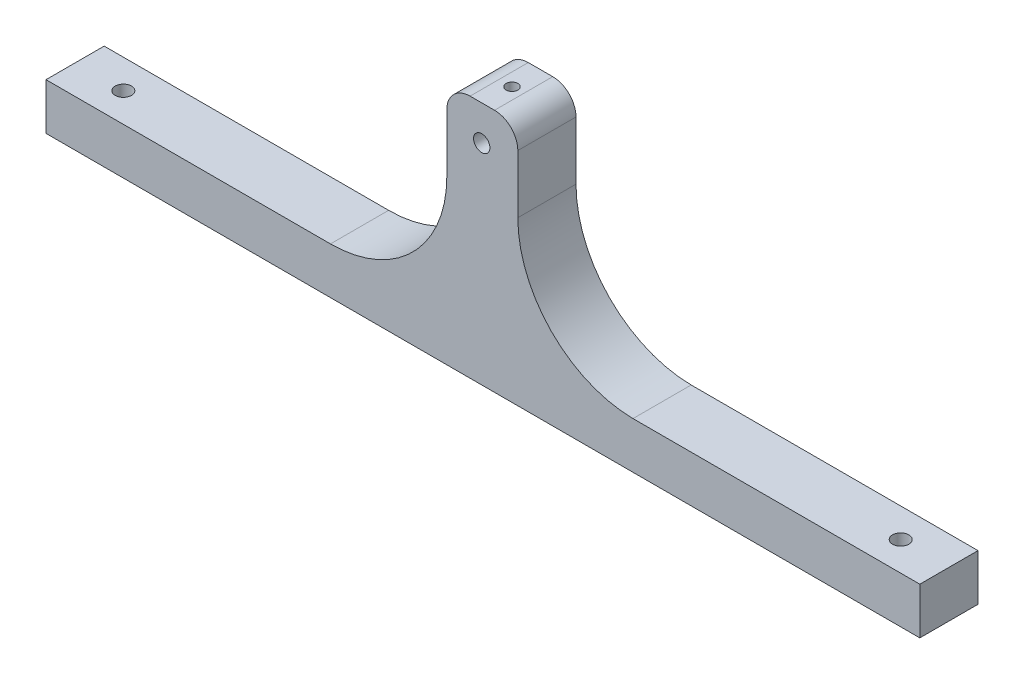
SolidWorks part; units mm, degrees
ref_plane "Front Plane" through (0, 0, 0) normal (0, 0, 1) x (1, 0, 0)
ref_plane "Top Plane" through (0, 0, 0) normal (0, 1, 0) x (1, 0, 0)
ref_plane "Right Plane" through (0, 0, 0) normal (1, 0, 0) x (0, 0, -1)
sketch "Sketch1" plane through (0, 0, 0) normal (0, 1, 0) x (1, 0, 0)
  line L0 (-37.55, 0) -> (37.55, 0) construction
  line L1 (-37.55, -2.5) -> (37.55, -2.5)
  line L2 (-37.55, -2.5) -> (-37.55, 2.5)
  line L3 (-37.55, 2.5) -> (37.55, 2.5)
  line L4 (37.55, -2.5) -> (37.55, 2.5)
  line L7 (0, 2.5) -> (0, -2.5) construction
  line L8 (-33.405, 2.5) -> (-33.405, -2.5) construction
  line L9 (33.405, 2.5) -> (33.405, -2.5) construction
  circle A0 centre (-33.405, 0) radius 0.7
  circle A1 centre (33.405, 0) radius 0.7
  circle A2 centre (0, 0) radius 0.5
  point P0 (0, 0)
  dimension "D1" = 75.1
  dimension "D2" = 5
  dimension "D3" = 66.81
  dimension "D4" = 33.405
extrude "Boss-Extrude1" add sketch "Sketch1" along normal blind 4
sketch "Sketch3" plane through (0, 0, 2.5) normal (0, 0, 1) x (1, 0, 0)
  line L0 (0, 0) -> (0, 19.7498) construction
  line L1 (-13.102, 4) -> (12.898, 4)
  line L5 (-3.102, 14) -> (-3.102, 19)
  line L6 (-1.102, 21) -> (1, 21)
  line L7 (3, 13.9995) -> (3, 19)
  line L8 (-3, 4) -> (3, 21) construction
  line L9 (-3.102, 21) -> (2.9925, 4.3) construction
  arc A0 (-13.102, 4) -> (-3.102, 14) centre (-13.102, 14) ccw
  arc A1 (12.898, 4) -> (3, 13.9995) centre (13, 13.9995) cw
  arc A2 (1, 21) -> (3, 19) centre (1, 19) cw
  arc A3 (-3.102, 19) -> (-1.102, 21) centre (-1.102, 19) cw
  point P11 (0, 12.5)
  dimension "D3" = 10
  dimension "D4" = 2
  dimension "D1" = 16.7
  dimension "D2" = 6
extrude "Boss-Extrude2" add sketch "Sketch3" against normal blind 5
sketch "Sketch4" plane through (0, 0, 0) normal (0, -1, 0) x (1, 0, 0)
  circle A0 centre (0, 0) radius 0.5 construction
  circle A1 centre (0, 0) radius 0.5
extrude "Cut-Extrude1" cut sketch "Sketch4" against normal blind 33
sketch "Sketch5" plane through (0, 0, 2.5) normal (0, 0, 1) x (1, 0, 0)
  line L0 (1, 21) -> (-1.102, 21) construction
  line L1 (-3.102, 19) -> (-3.102, 14) construction
  circle A0 centre (-0.102, 18) radius 0.703
  point P4 (0, 0)
  dimension "D1" = 3
  dimension "D2" = 3
extrude "Cut-Extrude2" cut sketch "Sketch5" against normal blind 10
